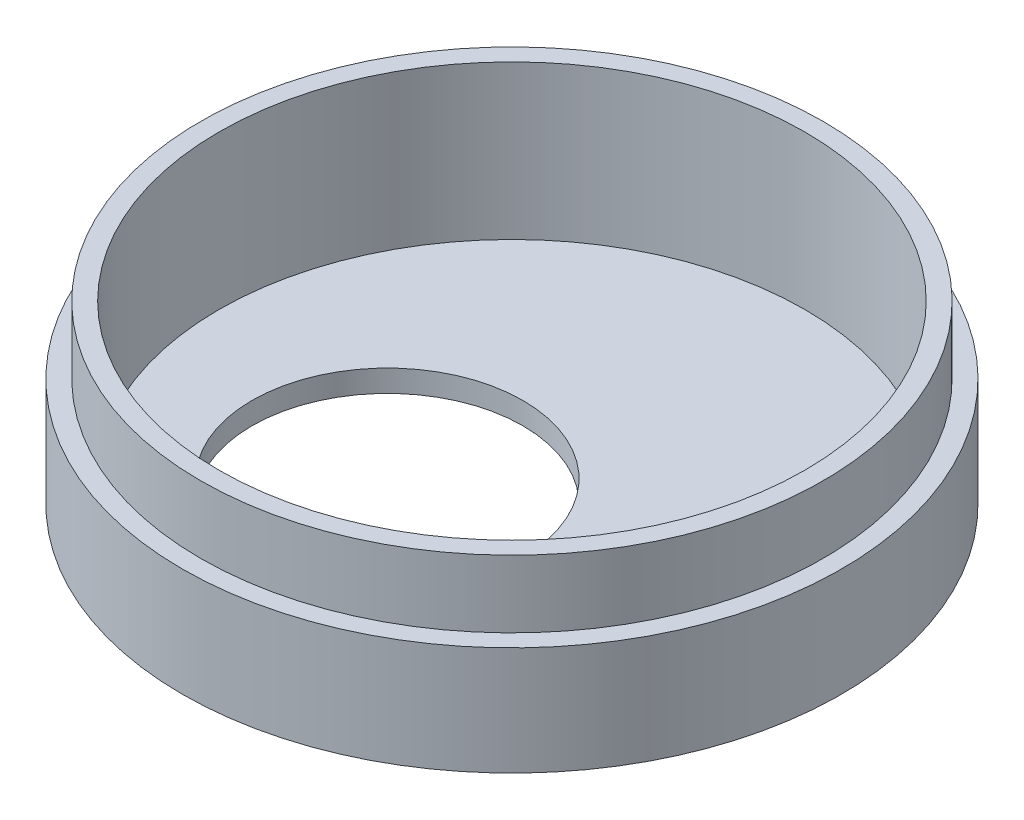
SolidWorks part; units mm, degrees
material "6061 Alloy"
ref_plane "Front Plane" through (0, 0, 0) normal (0, 0, 1) x (1, 0, 0)
ref_plane "Top Plane" through (0, 0, 0) normal (0, 1, 0) x (1, 0, 0)
ref_plane "Right Plane" through (0, 0, 0) normal (1, 0, 0) x (0, 0, -1)
sketch "Sketch1" plane through (0, 0, 0) normal (0, 0, 1) x (1, 0, 0)
  line L0 (22.86, 0) -> (22.86, -7.5247)
  line L1 (22.86, -7.5247) -> (0, -7.5247)
  line L2 (0, -7.5247) -> (0, -6.0007)
  line L3 (0, -6.0007) -> (20.955, -6.0007)
  line L4 (20.955, -6.0007) -> (20.955, 4.6672)
  line L5 (20.955, 4.6672) -> (22.225, 4.6672)
  line L6 (22.225, 4.6672) -> (22.225, 2.286)
  line L7 (22.225, 2.286) -> (21.59, 2.286)
  line L8 (21.59, 2.286) -> (21.59, 0)
  line L9 (21.59, 0) -> (22.225, 0)
  line L10 (22.225, 0) -> (22.86, 0)
  line L11 (20.955, 4.6672) -> (0, 4.6672) construction
  line L12 (0, 3.1432) -> (20.955, 3.1432) construction
  line L15 (0, 33.2677) -> (0, -75.4715) construction
  dimension "D1" = 22.86
  dimension "D2" = 0.635
  dimension "D3" = 1.905
  dimension "D4" = 1.524
  dimension "D5" = 0.635
  dimension "D6" = 2.286
  dimension "D7" = 0.635
  dimension "D8" = 2.3813
  dimension "D9" = 20.955
  dimension "D10" = 1.524
  dimension "D11" = 9.144
  dimension "D12" = 7.5247
revolve "Revolve1" add sketch "Sketch1" angle 360 about L15
sketch "Sketch2" plane through (0, 4.6672, 0) normal (0, 1, 0) x (1, 0, 0)
  circle A0 centre (0, 0) radius 22.225
  circle A1 centre (0, 0) radius 22.225 construction
  circle A2 centre (0, 0) radius 21.59
  circle A3 centre (0, 0) radius 21.59 construction
extrude "Cut-Extrude1" cut sketch "Sketch2" against normal up to next
sketch "Sketch3" plane through (0, -7.5247, 0) normal (0, -1, 0) x (1, 0, 0)
  circle A0 centre (-4.318, 4.318) radius 9.398
  circle A1 centre (0, 0) radius 22.86 construction
  point P2 (0, 22.86)
  point P8 (-4.318, 13.716)
  point P9 (-13.716, 4.318)
  point P10 (-22.86, 0)
  dimension "D1" = 18.796
  dimension "D2" = 9.144
  dimension "D3" = 9.144
extrude "Cut-Extrude2" cut sketch "Sketch3" against normal through all
sketch "Sketch5" plane through (0, 4.6672, 0) normal (0, 1, 0) x (1, 0, 0)
  circle A0 centre (0, 0) radius 20.955
  circle A1 centre (0, 0) radius 20.32
  circle A2 centre (0, 0) radius 20.955 construction
  dimension "D1" = 0.635
extrude "Boss-Extrude1" add sketch "Sketch5" against normal up to surface (10.668 mm away) up to face at (-4.318, -6.0007, -5.08)
